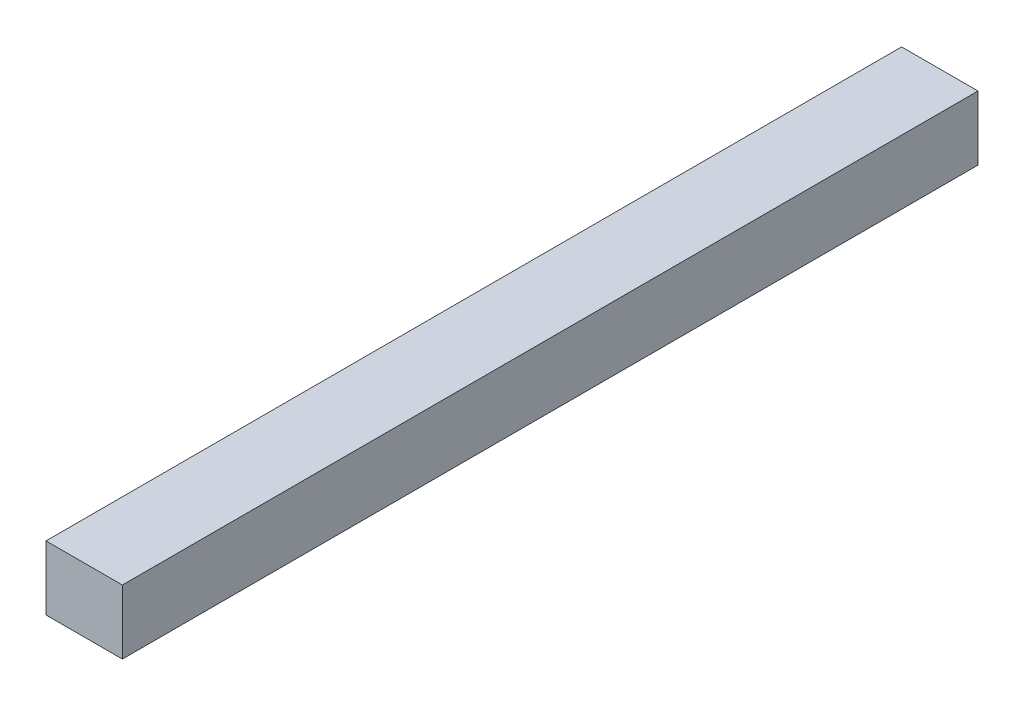
SolidWorks part; units mm, degrees
ref_plane "Plan de face" through (0, 0, 0) normal (0, 0, 1) x (1, 0, 0)
ref_plane "Plan de dessus" through (0, 0, 0) normal (0, 1, 0) x (1, 0, 0)
ref_plane "Plan de droite" through (0, 0, 0) normal (1, 0, 0) x (0, 0, -1)
sketch "Esquisse1" plane through (0, 0, 0) normal (0, 0, 1) x (1, 0, 0)
  line L1 (0, 0) -> (75, 0)
  line L2 (0, 0) -> (0, 63)
  line L3 (0, 63) -> (75, 63)
  line L4 (75, 0) -> (75, 63)
  dimension "D1" = 75
  dimension "D2" = 63
extrude "Boss.-Extru.1" add sketch "Esquisse1" along normal blind 840
